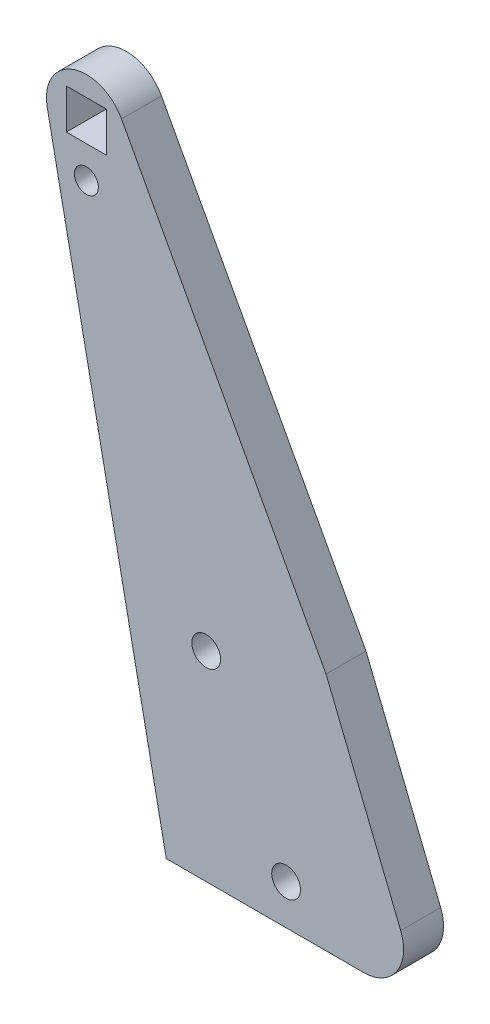
SolidWorks part; units mm, degrees
ref_plane "Front Plane" through (0, 0, 0) normal (0, 0, 1) x (1, 0, 0)
ref_plane "Top Plane" through (0, 0, 0) normal (0, 1, 0) x (1, 0, 0)
ref_plane "Right Plane" through (0, 0, 0) normal (1, 0, 0) x (0, 0, -1)
sketch "Sketch1" plane through (0, 0, 0) normal (0, 0, 1) x (1, 0, 0)
  line L1 (0, 0) -> (-25.4, 0)
  line L6 (-32.5135, 98.2688) -> (0, 38.1)
  line L7 (-44.3251, 93.9967) -> (-25.4, 0)
  line L9 (0, 38.1) -> (15.3934, 0)
  line L10 (15.3934, 0) -> (0, 0)
  line L11 (0, 38.1) -> (0, 0) construction
  line L13 (-41.275, 98.425) -> (-34.925, 98.425)
  line L14 (-41.275, 98.425) -> (-41.275, 92.075)
  line L15 (-41.275, 92.075) -> (-34.925, 92.075)
  line L16 (-34.925, 98.425) -> (-34.925, 92.075)
  line L17 (-41.275, 98.425) -> (-34.925, 92.075) construction
  line L18 (-41.275, 92.075) -> (-34.925, 98.425) construction
  arc A1 (-32.5135, 98.2688) -> (-44.3251, 93.9967) centre (-38.1, 95.25) ccw
  circle A2 centre (-6.35, 6.35) radius 2.286
  circle A3 centre (-19.05, 31.75) radius 2.286
  circle A6 centre (-38.1, 86.995) radius 1.905 construction
  circle A7 centre (-38.1, 86.995) radius 1.905
  dimension "D3" = 95.25
  dimension "D5" = 12.7
  dimension "D7" = 4.572
  dimension "D4" = 6.35
  dimension "D10" = 6.35
  dimension "D6" = 38.1
  dimension "D1" = 25.4
  dimension "D2" = 38.1
  dimension "D8" = 31.75
  dimension "D9" = 19.05
  dimension "D11" = 6.35
  dimension "D12" = 22
  dimension "D13" = 6.35
extrude "Boss-Extrude1" add sketch "Sketch1" against normal blind 6.35
fillet "Fillet1" radius 6.35 1 edges at (15.3934, 0, -3.175)
